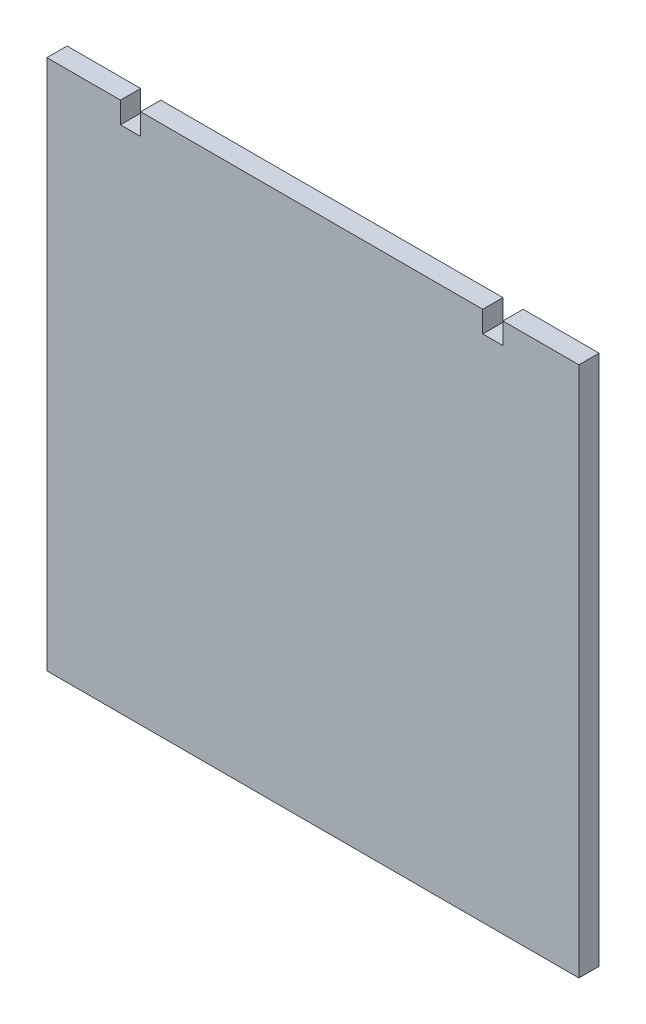
SolidWorks part; units mm, degrees
material "Acrylic (Medium-high impact)"
ref_plane "Front Plane" through (0, 0, 0) normal (0, 0, 1) x (1, 0, 0)
ref_plane "Top Plane" through (0, 0, 0) normal (0, 1, 0) x (1, 0, 0)
ref_plane "Right Plane" through (0, 0, 0) normal (1, 0, 0) x (0, 0, -1)
sketch "Sketch1" plane through (0, 0, 0) normal (0, 0, 1) x (1, 0, 0)
  line L0 (10.925, 78.867) -> (10.925, 75.692)
  line L1 (0, 0) -> (79, 0)
  line L2 (0, 0) -> (0, 78.867)
  line L3 (0, 78.867) -> (10.925, 78.867)
  line L4 (79, 0) -> (79, 78.867)
  line L5 (10.925, 75.692) -> (13.9222, 75.692)
  line L6 (13.9222, 75.692) -> (13.9222, 78.867)
  line L7 (39.3222, 78.867) -> (39.3222, 0) construction
  line L8 (64.7222, 75.692) -> (64.7222, 78.867)
  line L9 (67.7194, 75.692) -> (64.7222, 75.692)
  line L10 (67.7194, 78.867) -> (67.7194, 75.692)
  line L11 (13.9222, 78.867) -> (64.7222, 78.867)
  line L12 (67.7194, 78.867) -> (79, 78.867)
  dimension "D1" = 78.867
  dimension "D2" = 79
  dimension "D3" = 3.175
  dimension "D4" = 2.9972
  dimension "D5" = 25.4
  dimension "D6" = 10.925
extrude "Boss-Extrude1" add sketch "Sketch1" along normal blind 2.9972
